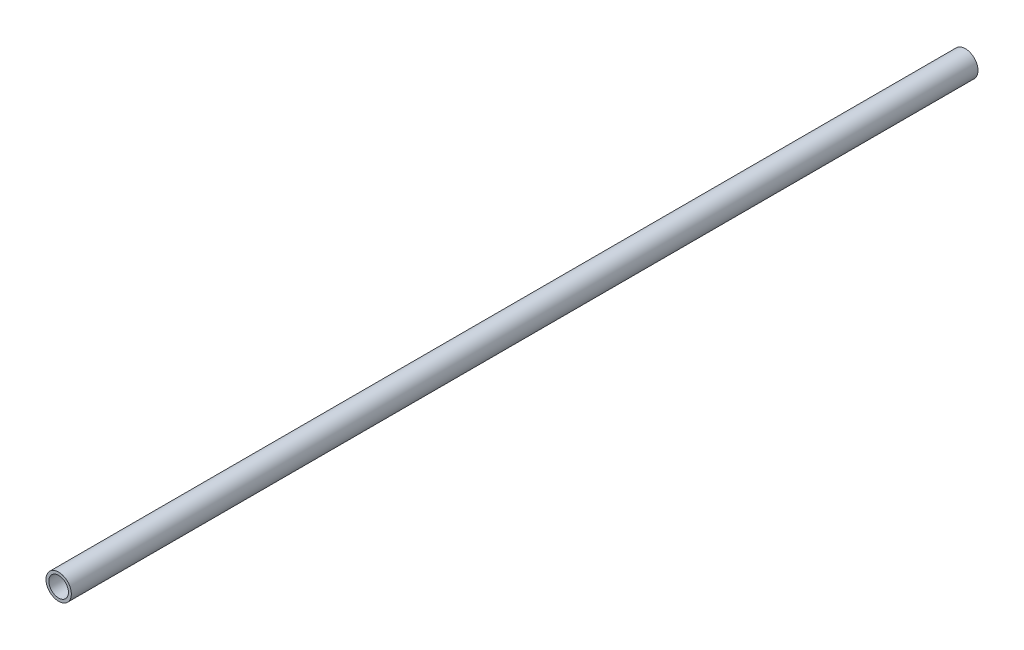
SolidWorks part; units mm, degrees
material "Hexcel AS4C (3000 Filaments)"
ref_plane "Front Plane" through (0, 0, 0) normal (0, 0, 1) x (1, 0, 0)
ref_plane "Top Plane" through (0, 0, 0) normal (0, 1, 0) x (1, 0, 0)
ref_plane "Right Plane" through (0, 0, 0) normal (1, 0, 0) x (0, 0, -1)
sketch "Sketch2" plane through (0, 0, 0) normal (0, 0, 1) x (1, 0, 0)
  circle A0 centre (0, 0) radius 4.7625
  circle A1 centre (0, 0) radius 3.683
  dimension "D1" = 9.525
  dimension "D2" = 7.366
extrude "Boss-Extrude1" add sketch "Sketch2" along normal mid plane 340.6189
